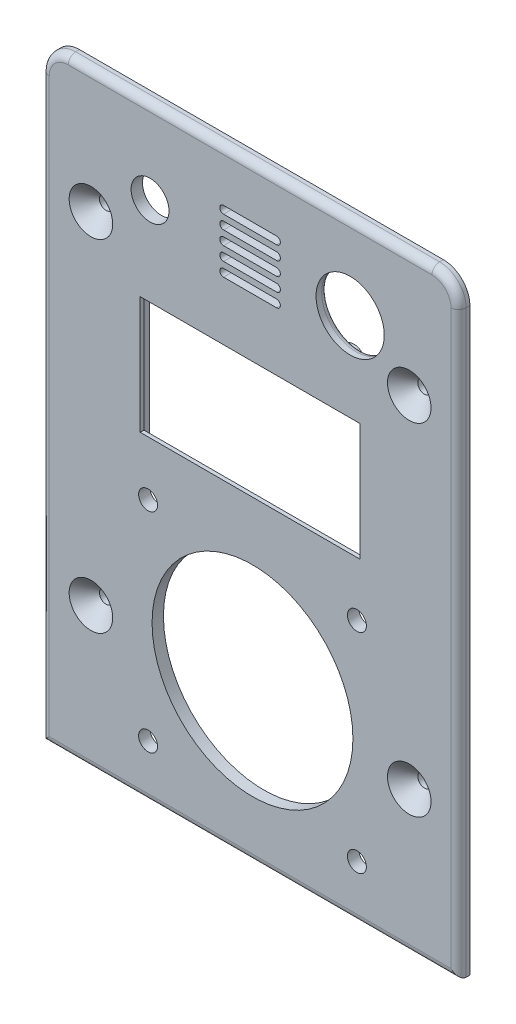
SolidWorks part; units mm, degrees
ref_plane "Front Plane" through (0, 0, 0) normal (0, 0, 1) x (1, 0, 0)
ref_plane "Top Plane" through (0, 0, 0) normal (0, 1, 0) x (1, 0, 0)
ref_plane "Right Plane" through (0, 0, 0) normal (1, 0, 0) x (0, 0, -1)
sketch "Sketch1" plane through (0, 0, 0) normal (0, 0, 1) x (1, 0, 0)
  line L1 (0, 0) -> (110, 0)
  line L2 (0, 0) -> (0, 153)
  line L3 (7, 160) -> (103, 160)
  line L4 (110, 0) -> (110, 153)
  arc A0 (103, 160) -> (110, 153) centre (103, 153) cw
  arc A1 (0, 153) -> (7, 160) centre (7, 153) cw
  point P7 (110, 160)
  point P10 (0, 160)
  dimension "D3" = 7
  dimension "D1" = 110
  dimension "D2" = 160
extrude "Boss-Extrude1" add sketch "Sketch1" along normal blind 3
fillet "Fillet1" radius 2 6 edges at (2.0503, 157.9497, 3) (55, 160, 3) (107.9497, 157.9497, 3) (110, 76.5, 3) (55, 0, 3) (0, 76.5, 3)
sketch "Sketch3" plane through (0, 0, 0) normal (0, 0, -1) x (-1, 0, 0)
  line L0 (0, 0) -> (-110, 0) construction
  line L1 (-103, 0) -> (-7, 0)
  line L2 (-103, 0) -> (-103, 152.5)
  line L3 (-103, 152.5) -> (-7, 152.5)
  line L4 (-7, 0) -> (-7, 152.5)
  line L5 (-101.4, 1.6) -> (-101.4, 33.5)
  line L6 (-101.4, 150.9) -> (-8.6, 150.9)
  line L7 (-8.6, 1.6) -> (-8.6, 33.5)
  line L8 (-101.4, 1.6) -> (-8.6, 1.6)
  line L9 (-97, 131.5) -> (-101.4, 131.5)
  line L10 (-97, 123.5) -> (-101.4, 123.5)
  line L11 (-13, 131.5) -> (-8.6, 131.5)
  line L12 (-8.6, 123.5) -> (-13, 123.5)
  line L13 (-13, 33.5) -> (-8.6, 33.5)
  line L14 (-13, 41.5) -> (-8.6, 41.5)
  line L15 (-97, 41.5) -> (-101.4, 41.5)
  line L16 (-101.4, 33.5) -> (-97, 33.5)
  line L17 (-101.4, 41.5) -> (-101.4, 123.5)
  line L18 (-8.6, 41.5) -> (-8.6, 123.5)
  line L19 (-101.4, 1.6) -> (-101.4, 150.9) construction
  line L20 (-8.6, 131.5) -> (-8.6, 150.9)
  line L21 (-8.6, 1.6) -> (-8.6, 150.9) construction
  line L22 (-101.4, 131.5) -> (-101.4, 150.9)
  arc A0 (-97, 123.5) -> (-97, 131.5) centre (-97, 127.5) ccw
  arc A1 (-13, 131.5) -> (-13, 123.5) centre (-13, 127.5) ccw
  arc A2 (-97, 33.5) -> (-97, 41.5) centre (-97, 37.5) ccw
  arc A3 (-13, 41.5) -> (-13, 33.5) centre (-13, 37.5) ccw
  point P6 (-55, 0)
  point P7 (-55, 0)
  dimension "D4" = 8
  dimension "D5" = 6
  dimension "D6" = 6
  dimension "D8" = 90
  dimension "D1" = 96
  dimension "D2" = 152.5
  dimension "D7" = 25
  dimension "D3" = 1.6
extrude "Boss-Extrude2" add sketch "Sketch3" along normal blind 3.9
sketch "Sketch4" plane through (0, 0, -3.9) normal (0, 0, -1) x (-1, 0, 0)
  circle A0 centre (-97, 127.5) radius 1.75
  circle A1 centre (-13, 127.5) radius 1.75
  circle A2 centre (-13, 37.5) radius 1.75
  circle A3 centre (-97, 37.5) radius 1.75
  dimension "D1" = 3.5
extrude "Cut-Extrude1" cut sketch "Sketch4" against normal up to next
chamfer "Chamfer1" distance 4 angle 45 4 edges at (95.25, 37.5, 3) (11.25, 37.5, 3) (11.25, 127.5, 3) (95.25, 127.5, 3)
sketch "Sketch5" plane through (0, 0, 0) normal (0, 0, -1) x (-1, 0, 0)
  line L0 (-8.6, 150.9) -> (-101.4, 150.9) construction
  line L1 (-8.6, 131.5) -> (-8.6, 150.9) construction
  line L2 (-101.4, 150.9) -> (-101.4, 131.5) construction
  circle A0 centre (-28.6, 137.9) radius 5
  circle A1 centre (-81.4, 137.9) radius 9
  dimension "D1" = 13
  dimension "D2" = 20
  dimension "D3" = 10
  dimension "D4" = 18
  dimension "D5" = 20
extrude "Cut-Extrude2" cut sketch "Sketch5" against normal through all
fillet "Fillet2" radius 1.5 1 edges at (72.4, 137.9, 0)
sketch "Sketch7" plane through (0, 0, 0) normal (0, 0, -1) x (-1, 0, 0)
  line L0 (-8.6, 150.9) -> (-101.4, 150.9) construction
  line L1 (-65, 147.9) -> (-45, 147.9)
  line L2 (-65, 147.9) -> (-65, 127.9)
  line L3 (-65, 127.9) -> (-45, 127.9)
  line L4 (-45, 147.9) -> (-45, 127.9)
  line L5 (-64, 146.9) -> (-46, 146.9)
  line L6 (-46, 146.9) -> (-46, 128.9)
  line L7 (-64, 128.9) -> (-46, 128.9)
  line L8 (-64, 146.9) -> (-64, 128.9)
  point P6 (-55, 150.9)
  point P7 (-55, 147.9)
  dimension "D1" = 20
  dimension "D2" = 20
  dimension "D3" = 3
  dimension "D4" = 1
extrude "Boss-Extrude3" add sketch "Sketch7" along normal up to surface (3.9 mm away) up to face at (95.25, 37.5, -3.9)
sketch "Sketch8" plane through (0, 0, 0) normal (0, 0, -1) x (-1, 0, 0)
  line L0 (-62, 145.4) -> (-48, 145.4) construction
  line L1 (-62, 146.4) -> (-48, 146.4)
  line L2 (-62, 144.4) -> (-48, 144.4)
  line L3 (-46, 146.9) -> (-64, 146.9) construction
  line L4 (-62, 141.8) -> (-48, 141.8) construction
  line L5 (-62, 142.8) -> (-48, 142.8)
  line L6 (-62, 140.8) -> (-48, 140.8)
  line L7 (-62, 138.2) -> (-48, 138.2) construction
  line L8 (-62, 139.2) -> (-48, 139.2)
  line L9 (-62, 137.2) -> (-48, 137.2)
  line L10 (-62, 134.6) -> (-48, 134.6) construction
  line L11 (-62, 135.6) -> (-48, 135.6)
  line L12 (-62, 133.6) -> (-48, 133.6)
  line L13 (-62, 131) -> (-48, 131) construction
  line L14 (-62, 132) -> (-48, 132)
  line L15 (-62, 130) -> (-48, 130)
  arc A0 (-62, 146.4) -> (-62, 144.4) centre (-62, 145.4) ccw
  arc A1 (-48, 144.4) -> (-48, 146.4) centre (-48, 145.4) ccw
  arc A2 (-62, 142.8) -> (-62, 140.8) centre (-62, 141.8) ccw
  arc A3 (-48, 140.8) -> (-48, 142.8) centre (-48, 141.8) ccw
  arc A4 (-62, 139.2) -> (-62, 137.2) centre (-62, 138.2) ccw
  arc A5 (-48, 137.2) -> (-48, 139.2) centre (-48, 138.2) ccw
  arc A6 (-62, 135.6) -> (-62, 133.6) centre (-62, 134.6) ccw
  arc A7 (-48, 133.6) -> (-48, 135.6) centre (-48, 134.6) ccw
  arc A8 (-62, 132) -> (-62, 130) centre (-62, 131) ccw
  arc A9 (-48, 130) -> (-48, 132) centre (-48, 131) ccw
  point P2 (-55, 145.4)
  point P9 (-55, 146.9)
  point P14 (-55, 141.8)
  point P21 (-55, 138.2)
  point P28 (-55, 134.6)
  point P35 (-55, 131)
  dimension "D2" = 1
  dimension "D1" = 14
  dimension "D3" = 1.5
  dimension "D4" = 5
extrude "Cut-Extrude3" cut sketch "Sketch8" against normal through all
sketch "Croquis1" plane through (0, 0, 0) normal (0, 0, -1) x (-1, 0, 0)
  circle A0 centre (-28.6, 116.15) radius 1.25
  circle A1 centre (-28.6, 116.15) radius 3
  circle A3 centre (-28.6, 116.15) radius 1.5 construction
  dimension "D1" = 2.5
  dimension "D2" = 6
extrude "Saliente-Extruir1" add sketch "Croquis1" along normal blind 5
sketch "Croquis2" plane through (0, 0, 0) normal (0, 0, -1) x (-1, 0, 0)
  line L0 (-8.6, 150.9) -> (-101.4, 150.9) construction
  line L1 (-92.4, 150.9) -> (-70.4, 150.9)
  line L2 (-92.4, 150.9) -> (-92.4, 147.9)
  line L3 (-92.4, 147.9) -> (-70.4, 147.9)
  line L4 (-70.4, 150.9) -> (-70.4, 147.9)
  line L5 (-91.4, 149.9) -> (-71.4, 149.9) construction
  circle A0 centre (-88.9, 120.4) radius 1.25
  circle A1 centre (-88.9, 120.4) radius 3
  circle A2 centre (-73.9, 120.4) radius 1.25
  circle A3 centre (-73.9, 120.4) radius 3
  point P16 (-81.4, 149.9)
  point P17 (-81.4, 147.9)
  dimension "D1" = 6
  dimension "D2" = 2.5
  dimension "D3" = 3
  dimension "D4" = 22
extrude "Saliente-Extruir2" add sketch "Croquis2" along normal blind 5.5
sketch "Croquis3" plane through (0, 0, 0) normal (0, 0, -1) x (-1, 0, 0)
  line L0 (-101.4, 1.6) -> (-8.6, 1.6) construction
  circle A0 centre (-55.6315, 41.6) radius 26.5
  dimension "D1" = 53
  dimension "45" = 40
extrude "Cortar-Extruir1" cut sketch "Croquis3" against normal up to next
sketch "Croquis4" plane through (0, 0, 0) normal (0, 0, -1) x (-1, 0, 0)
  line L1 (-88.1315, 9.1) -> (-23.1315, 9.1) construction
  line L2 (-88.1315, 9.1) -> (-88.1315, 74.1) construction
  line L3 (-88.1315, 74.1) -> (-23.1315, 74.1) construction
  line L4 (-23.1315, 9.1) -> (-23.1315, 74.1) construction
  line L5 (-88.1315, 9.1) -> (-23.1315, 74.1) construction
  line L6 (-88.1315, 74.1) -> (-23.1315, 9.1) construction
  circle A0 centre (-83.1818, 69.1503) radius 2.5
  circle A1 centre (-28.0813, 69.1503) radius 2.5
  circle A2 centre (-28.0813, 14.0497) radius 2.5
  circle A3 centre (-83.1818, 14.0497) radius 2.5
  point P0 (-55.6315, 41.6)
  dimension "D2" = 5
  dimension "D1" = 65
  dimension "D3" = 7
extrude "Cortar-Extruir2" cut sketch "Croquis4" against normal up to next contours A0
sketch "Croquis5" plane through (0, 0, 0) normal (0, 0, -1) x (-1, 0, 0)
  line L0 (-101.4, 95.543) -> (-8.6, 95.543) construction
  line L1 (-101.4, 123.5) -> (-101.4, 41.5) construction
  line L2 (-8.6, 41.5) -> (-8.6, 123.5) construction
  line L4 (-84.5, 75.543) -> (-25.5, 75.543)
  line L5 (-84.5, 75.543) -> (-84.5, 115.543)
  line L6 (-84.5, 115.543) -> (-25.5, 115.543)
  line L7 (-25.5, 75.543) -> (-25.5, 115.543)
  line L8 (-84.5, 75.543) -> (-25.5, 115.543) construction
  line L9 (-84.5, 115.543) -> (-25.5, 75.543) construction
  point P6 (-55, 95.543)
  dimension "D1" = 40
  dimension "D2" = 59
extrude "Cortar-Extruir3" cut sketch "Croquis5" against normal blind 2
sketch "Croquis6" plane through (0, 0, 2) normal (0, 0, -1) x (-1, 0, 0)
  line L0 (-84.5, 115.543) -> (-84.5, 75.543) construction
  line L1 (-84, 114.543) -> (-26, 114.543)
  line L2 (-84.5, 114.543) -> (-84.5, 83.543) construction
  line L3 (-84, 83.543) -> (-26, 83.543)
  line L4 (-25.5, 114.543) -> (-25.5, 83.543) construction
  line L5 (-25.5, 75.543) -> (-25.5, 115.543) construction
  line L6 (-25.5, 115.543) -> (-84.5, 115.543) construction
  line L7 (-26, 114.543) -> (-26, 83.543)
  line L8 (-84, 114.543) -> (-84, 83.543)
  dimension "D1" = 31
  dimension "D2" = 1
  dimension "D3" = 0.5
  dimension "D4" = 0.5
extrude "Cortar-Extruir4" cut sketch "Croquis6" against normal blind 2
